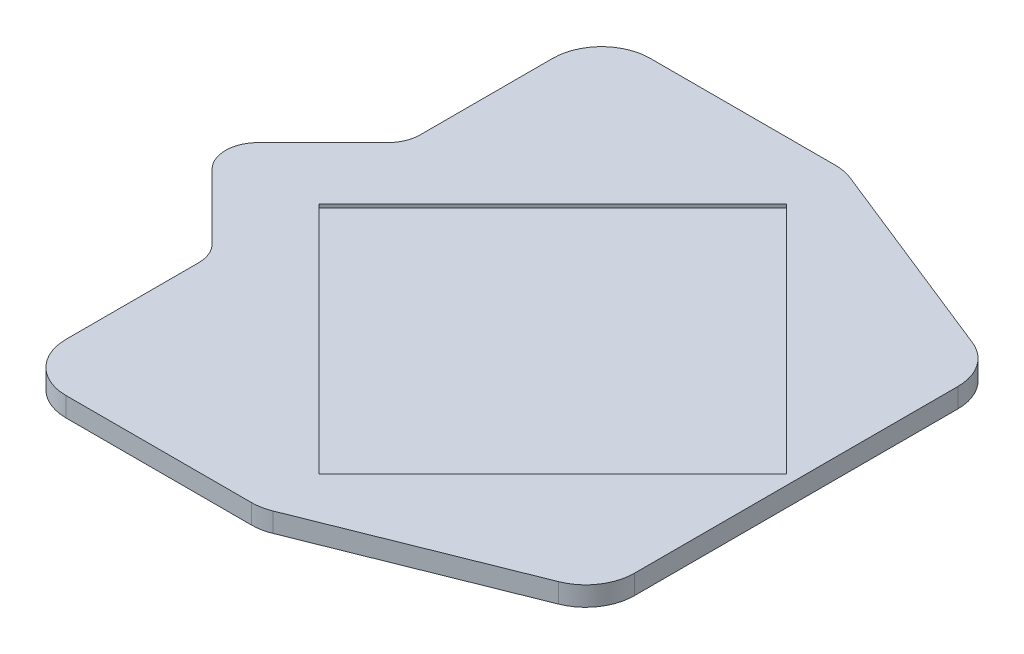
SolidWorks part; units mm, degrees
material "环氧树脂,未充填"
ref_plane "前视基准面" through (0, 0, 0) normal (0, 0, 1) x (1, 0, 0)
ref_plane "上视基准面" through (0, 0, 0) normal (0, 1, 0) x (1, 0, 0)
ref_plane "右视基准面" through (0, 0, 0) normal (1, 0, 0) x (0, 0, -1)
sketch "草图1" plane through (0, 0, 0) normal (0, 1, 0) x (1, 0, 0)
  line L0 (12.5, 0) -> (25, -5)
  line L1 (0, 0) -> (12.5, 0)
  line L2 (0, 0) -> (0, -30)
  line L3 (0, -30) -> (12.5, -30)
  line L4 (12.5, 0) -> (12.5, -30)
  line L5 (12.5, 0) -> (25, 0)
  line L6 (12.5, 0) -> (12.5, -30)
  line L7 (12.5, -30) -> (25, -30)
  line L8 (25, 0) -> (25, -30)
  line L9 (25, -5) -> (25, -25)
  line L10 (25, -25) -> (12.5, -30)
  line L11 (0, -15) -> (-5, -15)
  line L12 (-5, -15) -> (0, -10)
  line L13 (0, -10) -> (0, -20)
  line L14 (0, -20) -> (-5, -15)
  dimension "D1" = 30
  dimension "D2" = 12.5
  dimension "D3" = 12.5
  dimension "D4" = 5
  dimension "D5" = 20
  dimension "D6" = 5
  dimension "D7" = 5
  dimension "D8" = 5
extrude "凸台-拉伸1" add sketch "草图1" along normal blind 1 contours L4 L1 L2 L3 | L10 L8 L0 L4 | L12 L11 L2 | L14 L2 L11
scale "缩放比例1" bodies to scale 106 scale about centroid uniform scaling yes scale factor 1.2
fillet "圆角1" radius 2 1 edges at (-8.2544, 0.5, 15)
fillet "圆角2" radius 3 6 edges at (12.7456, 0.5, 33) (-2.2544, 0.5, 33) (27.7456, 0.5, 27) (27.7456, 0.5, 3) (12.7456, 0.5, -3) (-2.2544, 0.5, -3)
fillet "圆角3" radius 2 2 edges at (-2.2544, 0.5, 21) (-2.2544, 0.5, 9)
sketch "草图2" plane through (0, 1.1, 0) normal (0, 1, 0) x (1, 0, 0)
  line L0 (-5.426, -15) -> (32.6789, -15) construction
  line L1 (12.7352, 2.9459) -> (12.7352, -32.9459) construction
  line L3 (27.146, -15) -> (12.7352, -0.5892)
  line L4 (12.7352, -0.5892) -> (-1.6756, -15)
  line L5 (-1.6756, -15) -> (12.7352, -29.4108)
  line L6 (12.7352, -29.4108) -> (27.146, -15)
  arc A0 (13.282, 2.7854) -> (12.1679, 3) centre (12.1679, 0) ccw construction
  arc A1 (12.1679, -33) -> (13.282, -32.7854) centre (12.1679, -30) ccw construction
  circle A2 centre (12.7352, -15) radius 10.19 construction
  dimension "D1" = 20.38
extrude "切除-拉伸1" cut sketch "草图2" against normal blind 0.2
